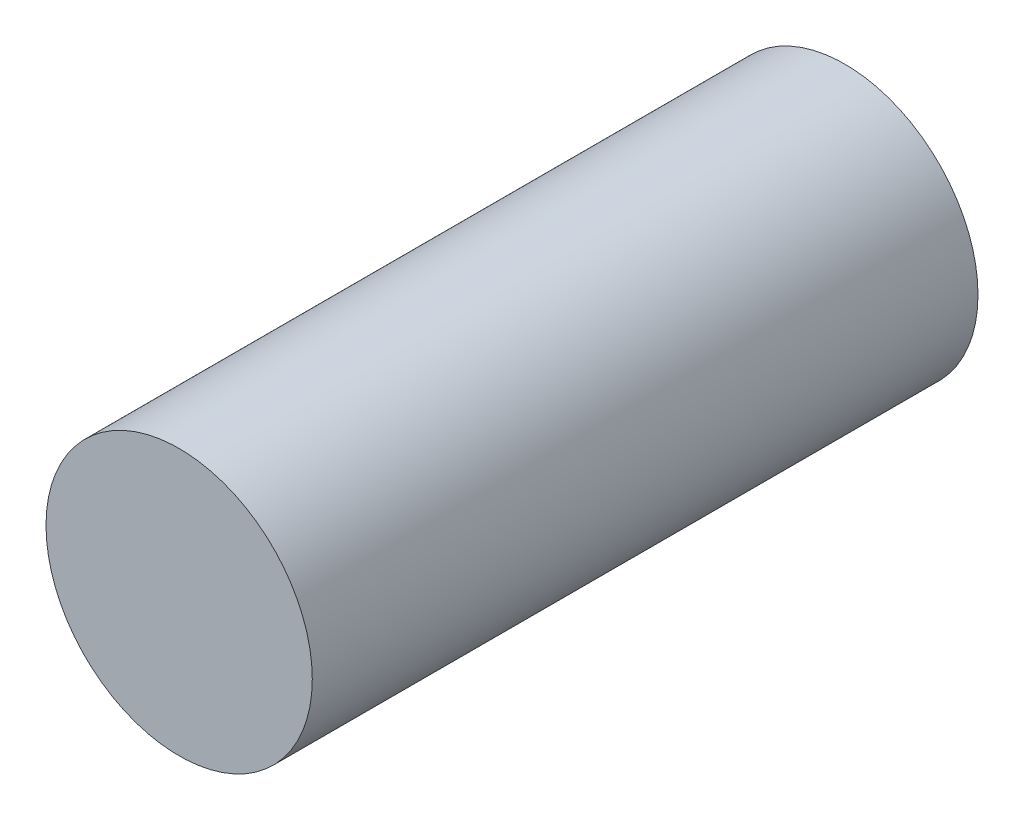
SolidWorks part; units mm, degrees
ref_plane "前视基准面" through (0, 0, 0) normal (0, 0, 1) x (1, 0, 0)
ref_plane "上视基准面" through (0, 0, 0) normal (0, 1, 0) x (1, 0, 0)
ref_plane "右视基准面" through (0, 0, 0) normal (1, 0, 0) x (0, 0, -1)
other "Configuration Table"
sketch "草图1" plane through (0, 0, 0) normal (0, 0, 1) x (1, 0, 0)
  circle A0 centre (0, 0) radius 6
  dimension "D1" = 12
extrude "凸台-拉伸1" add sketch "草图1" along normal blind 30
